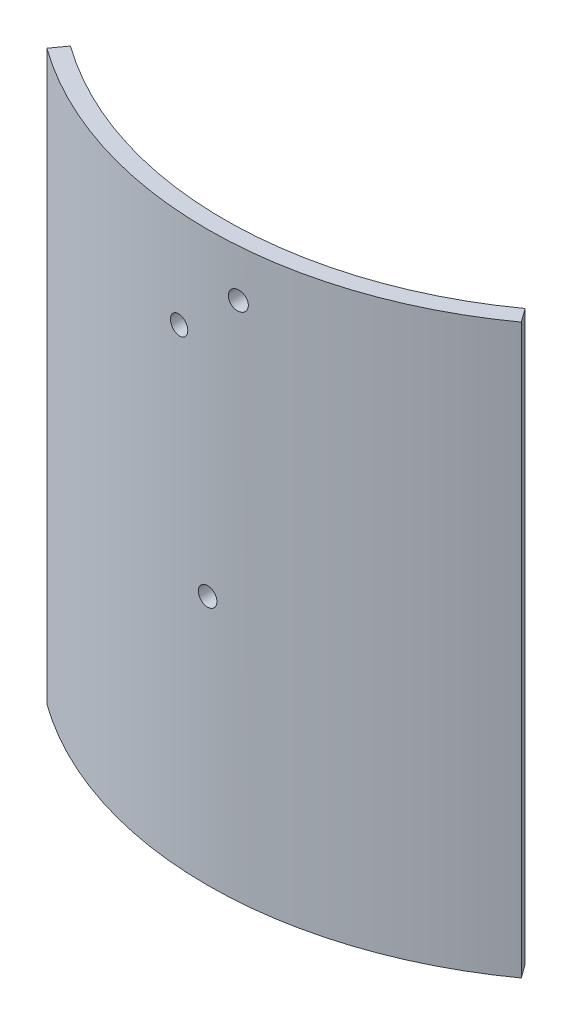
SolidWorks part; units mm, degrees
ref_plane "Front Plane" through (0, 0, 0) normal (0, 0, 1) x (1, 0, 0)
ref_plane "Top Plane" through (0, 0, 0) normal (0, 1, 0) x (1, 0, 0)
ref_plane "Right Plane" through (0, 0, 0) normal (1, 0, 0) x (0, 0, -1)
sketch "Sketch1" plane through (0, 0, 0) normal (0, 1, 0) x (1, 0, 0)
  line L5 (0, 0) -> (0, -76.2) construction
  line L6 (44.5485, -76.2) -> (-44.5485, -76.2) construction
  line L7 (-44.5485, -76.2) -> (-44.5485, -61.8213) construction
  line L8 (44.5485, -76.2) -> (44.5485, -61.8213) construction
  line L9 (-42.6923, -59.2454) -> (-44.5485, -61.8213)
  line L10 (42.6923, -59.2454) -> (44.5485, -61.8213)
  circle A0 centre (0, 0) radius 76.2 construction
  circle A2 centre (0, 0) radius 73.025 construction
  arc A4 (44.5485, -61.8213) -> (-44.5485, -61.8213) centre (0, 0) cw
  arc A5 (42.6923, -59.2454) -> (-42.6923, -59.2454) centre (0, 0) cw
  point P7 (0, -76.2)
extrude "Boss-Extrude1" add sketch "Sketch1" along normal blind 114.3
ref_plane "Plane1" through (0, 0, 59.2454) normal (0, 0, -1) x (-1, 0, 0)
sketch "Sketch2" plane through (0, 0, 59.2454) normal (0, 0, -1) x (-1, 0, 0)
  line L0 (0, 114.3) -> (0, 105.41) construction
  line L1 (42.6923, 114.3) -> (-42.6923, 114.3) construction
  line L2 (0, 114.3) -> (0, 95.885) construction
  line L3 (0, 114.3) -> (0, 54.61) construction
  line L4 (0, 105.41) -> (-5.5562, 105.41) construction
  line L5 (0, 95.885) -> (5.5563, 95.885) construction
  circle A0 centre (0, 54.61) radius 1.7526
  circle A1 centre (-5.5562, 105.41) radius 1.7526
  circle A2 centre (5.5563, 95.885) radius 1.7526
extrude "Cut-Extrude1" cut sketch "Sketch2" against normal blind 25.4
sketch "Sketch3" plane through (0, 0, 59.2454) normal (0, 0, -1) x (-1, 0, 0)
  line L0 (0, 0) -> (0, 7.62) construction
  line L1 (-44.5485, 7.62) -> (44.5485, 7.62)
  line L2 (-44.5485, 114.3) -> (-44.5485, 0) construction
  line L3 (44.5485, 114.3) -> (44.5485, 0) construction
  line L4 (-44.5485, 7.62) -> (44.5485, 7.62)
  line L5 (-44.5485, 7.62) -> (-44.5485, -4.0528)
  line L6 (44.5485, 7.62) -> (44.5485, -4.0528)
  line L7 (-44.5485, -4.0528) -> (44.5485, -4.0528)
extrude "Cut-Extrude2" cut sketch "Sketch3" against normal blind 25.4
